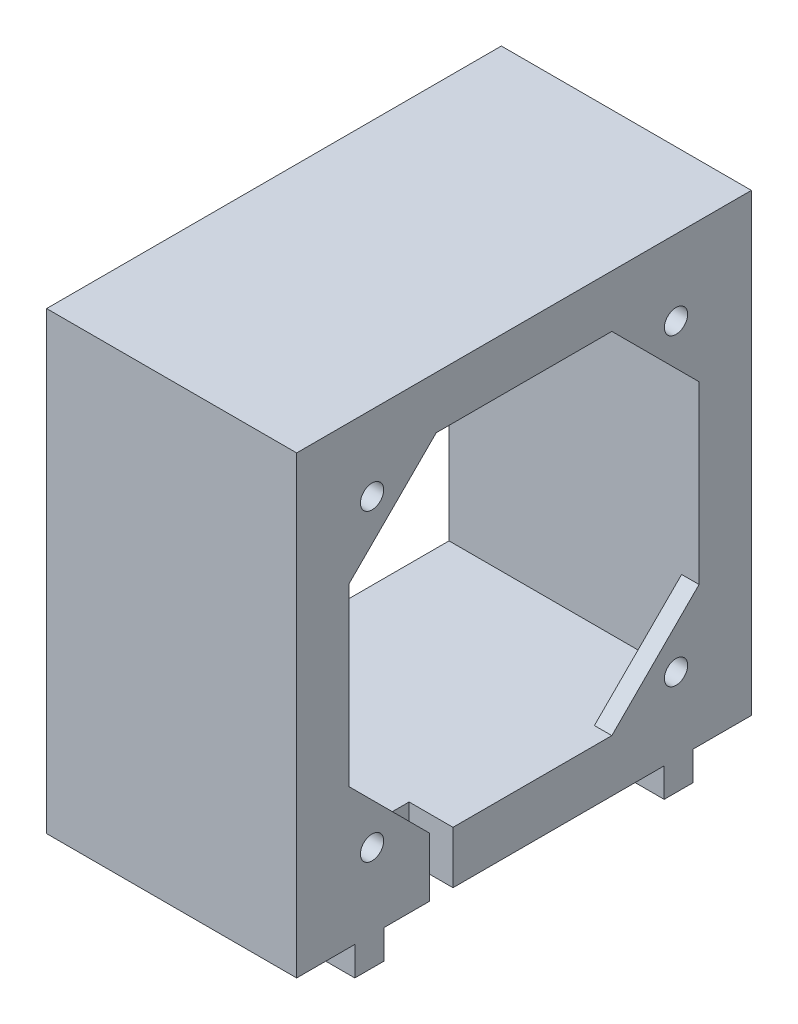
SolidWorks part; units mm, degrees
ref_plane "Front Plane" through (0, 0, 0) normal (0, 0, 1) x (1, 0, 0)
ref_plane "Top Plane" through (0, 0, 0) normal (0, 1, 0) x (1, 0, 0)
ref_plane "Right Plane" through (0, 0, 0) normal (1, 0, 0) x (0, 0, -1)
sketch "Sketch1" plane through (0, 0, 0) normal (1, 0, 0) x (0, 0, -1)
  line L1 (30.1, 30.1) -> (-30.1, 30.1)
  line L2 (30.1, 30.1) -> (30.1, -30.1)
  line L3 (30.1, -30.1) -> (-30.1, -30.1)
  line L4 (-30.1, 30.1) -> (-30.1, -30.1)
  line L5 (30.1, 30.1) -> (-30.1, -30.1) construction
  line L6 (30.1, -30.1) -> (-30.1, 30.1) construction
  line L7 (39.1, 39.1) -> (-39.1, 39.1)
  line L8 (39.1, 39.1) -> (39.1, -39.1)
  line L9 (39.1, -39.1) -> (-39.1, -39.1)
  line L10 (-39.1, 39.1) -> (-39.1, -39.1)
  line L11 (39.1, 39.1) -> (-39.1, -39.1) construction
  line L12 (39.1, -39.1) -> (-39.1, 39.1) construction
  point P0 (0, 0)
  point P6 (0, 0)
  dimension "D1" = 60.2
  dimension "D2" = 60.2
  dimension "D3" = 9
extrude "Boss-Extrude1" add sketch "Sketch1" along normal blind 40
sketch "Sketch2" plane through (40, 0, 0) normal (1, 0, 0) x (0, 0, -1)
  line L0 (-30.1, 30.1) -> (-30.1, -30.1)
  line L1 (-30.1, -30.1) -> (30.1, -30.1)
  line L2 (30.1, -30.1) -> (30.1, 30.1)
  line L3 (30.1, 30.1) -> (-30.1, 30.1)
  line L4 (-15.1, 30.1) -> (-30.1, 15.1)
  line L5 (30.1, 15.1) -> (15.1, 30.1)
  line L6 (15.1, -30.1) -> (30.1, -15.1)
  line L7 (-30.1, -15.1) -> (-15.1, -30.1)
  line L8 (-22.6, 22.6) -> (-30.1, 30.1) construction
  circle A0 centre (-26.1355, 26.1355) radius 2
  circle A1 centre (26.1355, 26.1355) radius 2
  circle A2 centre (26.1355, -26.1355) radius 2
  circle A3 centre (-26.1355, -26.1355) radius 2
  point P19 (0, 0)
  point P29 (0, 0)
  line M9 (-39.1, 39.1) -> (-39.1, -39.1)
  line M10 (-39.1, -39.1) -> (39.1, -39.1)
  line M11 (39.1, -39.1) -> (39.1, 39.1)
  line M12 (39.1, 39.1) -> (-39.1, 39.1)
  line M13 (-30.1, -30.1) -> (-30.1, 30.1)
  line M14 (-30.1, 30.1) -> (30.1, 30.1)
  line M15 (30.1, 30.1) -> (30.1, -30.1)
  line M16 (30.1, -30.1) -> (-30.1, -30.1)
  dimension "D7" = 4
  dimension "D1" = 15
  dimension "D2" = 15
  dimension "D4" = 30.2
  dimension "D5" = 15
  dimension "D6" = 5
  dimension "D3" = 4
  dimension "D8" = 4
extrude "Boss-Extrude2" add sketch "Sketch2" along normal blind 3 contours L4 L8 A0 L0 | L8 L4 A0 M14 | L5 A1 M15 M14 | L6 A2 M16 M15 | L7 A3 M13 M16 | L1 L0 L3 L2 M12 M9 M10 M11 M16 M13 M14 M15
sketch "Sketch3" plane through (0, -30.1, 0) normal (0, 1, 0) x (1, 0, 0)
  line L0 (43, 15.1) -> (43, -15.1) construction
  line L1 (50.5492, -16.2155) -> (35.4508, -16.2155)
  line L2 (50.5492, -16.2155) -> (50.5492, -12.2155)
  line L3 (50.5492, -12.2155) -> (35.4508, -12.2155)
  line L4 (35.4508, -16.2155) -> (35.4508, -12.2155)
  line L5 (50.5492, -16.2155) -> (35.4508, -12.2155) construction
  line L6 (50.5492, -12.2155) -> (35.4508, -16.2155) construction
  point P0 (43, -14.2155)
  dimension "D1" = 4
extrude "Cut-Extrude1" cut sketch "Sketch3" against normal mid plane 38
sketch "Sketch4" plane through (0, 0, 0) normal (-1, 0, 0) x (0, 0, 1)
  line L0 (30.1, 30.1) -> (39.1, 39.1)
  line L2 (-39.1, 39.1) -> (-30.1, 30.1) construction
  circle A0 centre (34.6, 34.6) radius 4.1
  circle A1 centre (34.6, -34.6) radius 4.1
  circle A2 centre (-34.6, -34.6) radius 4.1
  circle A3 centre (-34.6, 34.6) radius 4.1
  point P11 (34.6, 34.6)
  point P13 (-34.6, 34.6)
  point P16 (0, 0)
  dimension "D1" = 8.2
  dimension "D2" = 4
extrude "Cut-Extrude2" cut sketch "Sketch4" against normal mid plane 2.2 contours A3 | A2 | A1 | L0 A0 | L0 A0
sketch "Sketch5" plane through (0, -39.1, 0) normal (0, -1, 0) x (1, 0, 0)
  line L7 (13, -29.1) -> (43, -29.1)
  line L8 (13, -29.1) -> (13, -24.1)
  line L9 (13, -24.1) -> (43, -24.1)
  line L10 (43, -29.1) -> (43, -24.1)
  line L12 (13, 29.1) -> (43, 29.1)
  line L13 (13, 29.1) -> (13, 24.1)
  line L14 (13, 24.1) -> (43, 24.1)
  line L15 (43, 29.1) -> (43, 24.1)
  line L16 (43, 39.1) -> (0, 39.1) construction
  line L17 (43, -39.1) -> (0, -39.1) construction
  line L18 (43, 39.1) -> (43, 16.2155) construction
  line L19 (43, 12.2155) -> (43, -39.1) construction
  point P19 (43, 24.1)
  point P22 (43, -29.1)
  dimension "D1" = 10
  dimension "D2" = 10
  dimension "D3" = 5
  dimension "D4" = 5
  dimension "D5" = 30
  dimension "D6" = 30
extrude "Boss-Extrude3" add sketch "Sketch5" along normal blind 5
